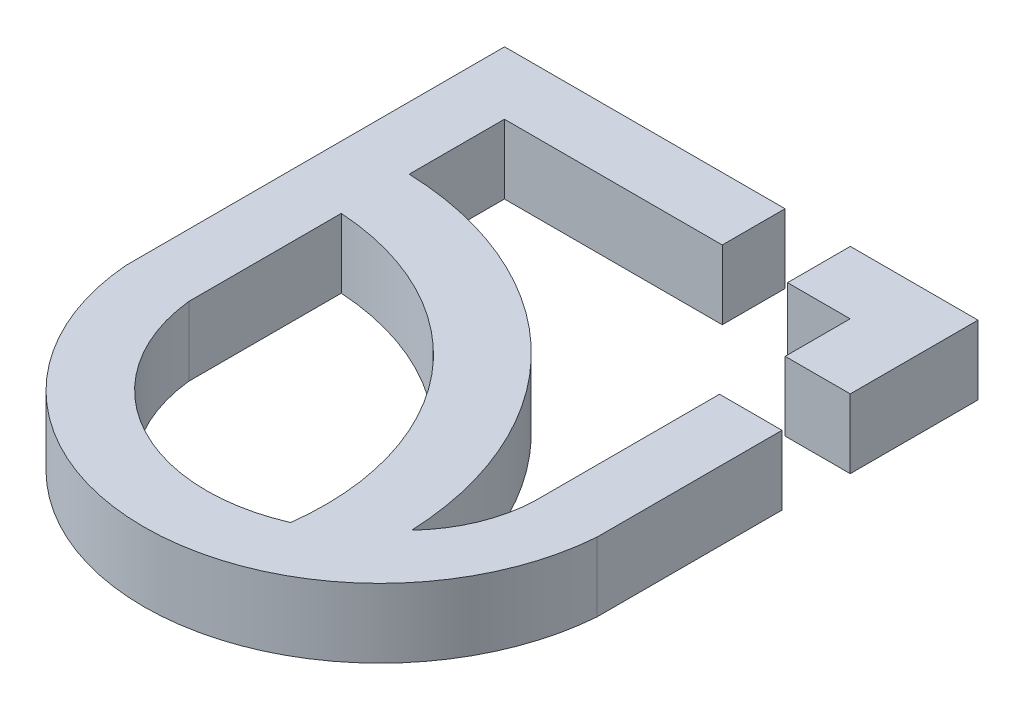
SolidWorks part; units mm, degrees
ref_plane "Front Plane" through (0, 0, 0) normal (0, 0, 1) x (1, 0, 0)
ref_plane "Top Plane" through (0, 0, 0) normal (0, 1, 0) x (1, 0, 0)
ref_plane "Right Plane" through (0, 0, 0) normal (1, 0, 0) x (0, 0, -1)
sketch "Sketch1" plane through (0, 0, 0) normal (0, 1, 0) x (1, 0, 0)
  line L0 (29, 109.5) -> (145, 109.5) construction
  line L1 (0, 0) -> (0, 116.767) construction
  line L2 (23.0118, 80.0276) -> (150.0261, 80.0276) construction
  line L3 (0, 80.0276) -> (0, 219.0676)
  line L4 (0, 219.0676) -> (103.0401, 219.0676)
  line L5 (103.0401, 219.0676) -> (103.0401, 195.9995)
  line L6 (103.0401, 195.9995) -> (23.0118, 195.9995)
  line L7 (23.0118, 195.9995) -> (23.0118, 161.0132)
  line L8 (150.0261, 80.0276) -> (150.0261, 148.0117)
  line L9 (150.0261, 148.0117) -> (172.9743, 148.0117)
  line L10 (172.9743, 80.0276) -> (172.9743, 148.0117)
  line L11 (172.9743, 80.0276) -> (175.6962, 80.0276) construction
  line L12 (103.0401, 219.0676) -> (173.9279, 219.0676) construction
  line L13 (23.0118, 136.0582) -> (23.0118, 80.0276)
  line L14 (173.9279, 219.0676) -> (173.9279, 172.1301) construction
  line L16 (173.9279, 172.1301) -> (150.0261, 172.1301)
  line L17 (173.9279, 172.1301) -> (173.9279, 219.0676)
  line L18 (173.9279, 219.0676) -> (127.0177, 219.0676)
  line L19 (127.0177, 195.9995) -> (127.0177, 219.0676)
  line L22 (127.0177, 195.9995) -> (150.0261, 195.9995)
  line L23 (150.0261, 172.1301) -> (150.0261, 195.9995)
  arc A0 (0, 80.0276) -> (172.9743, 80.0276) centre (86.4872, 86.7884) ccw
  arc A1 (23.0118, 80.0276) -> (112.0664, 28.4105) centre (86.519, 86.9649) ccw
  arc A2 (23.0118, 161.0132) -> (136.7449, 48.2112) centre (18.9852, 43.2164) cw
  arc A3 (23.0118, 136.0582) -> (112.0664, 28.4105) centre (17.0299, 40.4491) cw
  arc A4 (136.7449, 48.2112) -> (150.0261, 80.0276) centre (101.1223, 81.7615) ccw
extrude "Boss-Extrude1" add sketch "Sketch1" along normal blind 25.4
